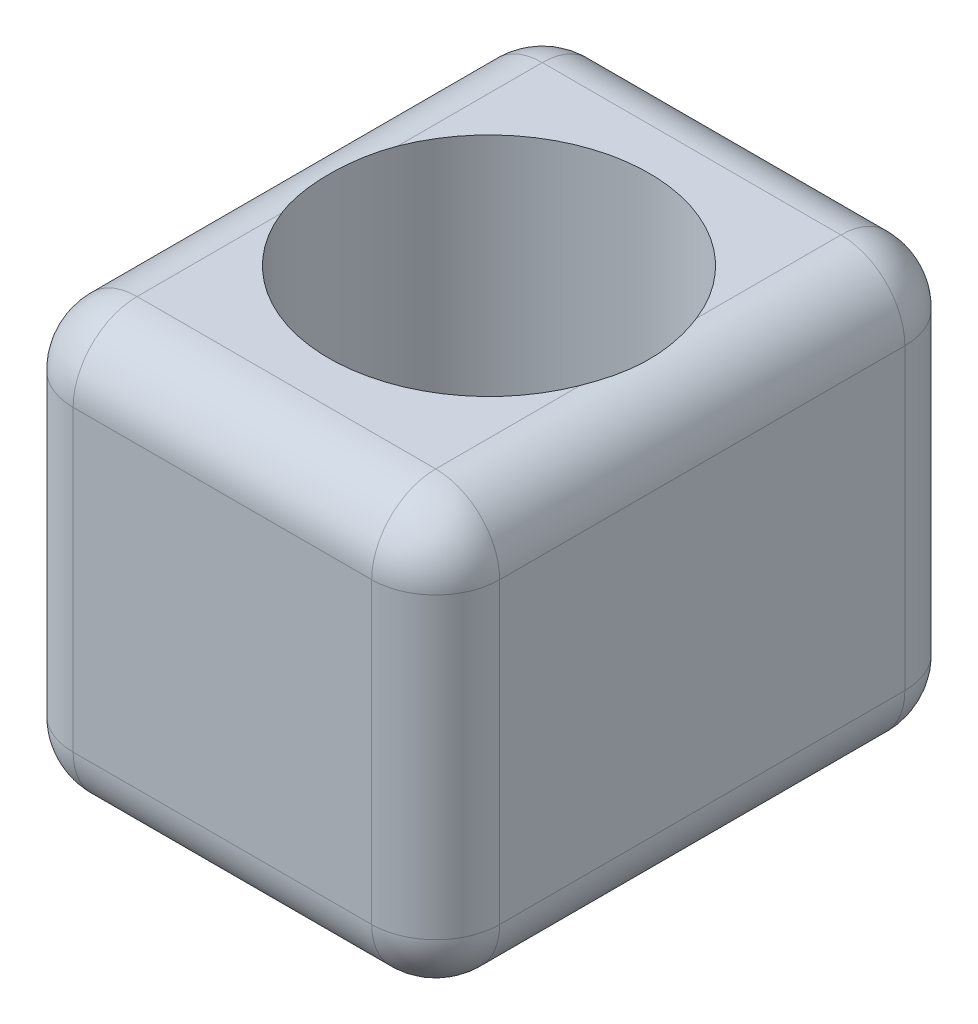
SolidWorks part; units mm, degrees
ref_plane "Ön Düzlem" through (0, 0, 0) normal (0, 0, 1) x (1, 0, 0)
ref_plane "Üst Düzlem" through (0, 0, 0) normal (0, 1, 0) x (1, 0, 0)
ref_plane "Sağ Düzlem" through (0, 0, 0) normal (1, 0, 0) x (0, 0, -1)
sketch "Sketch1" plane through (0, 0, 0) normal (0, 0, 1) x (1, 0, 0)
  line L1 (-20, 20) -> (20, 20)
  line L2 (-20, 20) -> (-20, -20)
  line L3 (-20, -20) -> (20, -20)
  line L4 (20, 20) -> (20, -20)
  line L5 (-20, 20) -> (20, -20) construction
  line L6 (-20, -20) -> (20, 20) construction
  point P0 (0, 0)
  dimension "D1" = 40
  dimension "D2" = 40
extrude "Boss-Extrude1" add sketch "Sketch1" along normal blind 50
fillet "Fillet1" radius 6 12 edges at (-20, 0, 0) (20, 0, 0) (-20, 0, 50) (20, 0, 50) (-20, -20, 25) (0, -20, 50) (20, -20, 25) (0, -20, 0) (20, 20, 25) (0, 20, 50) (-20, 20, 25) (0, 20, 0)
sketch "Sketch2" plane through (0, 20, 0) normal (0, 1, 0) x (1, 0, 0)
  line L0 (14, -6) -> (-14, -6) construction
  line L1 (14, -44) -> (14, -6) construction
  circle A0 centre (0, -25) radius 15.025
  point P5 (0, -6)
  point P9 (14, -25)
  dimension "D1" = 30.05
extrude "Cut-Extrude1" cut sketch "Sketch2" against normal blind 50
